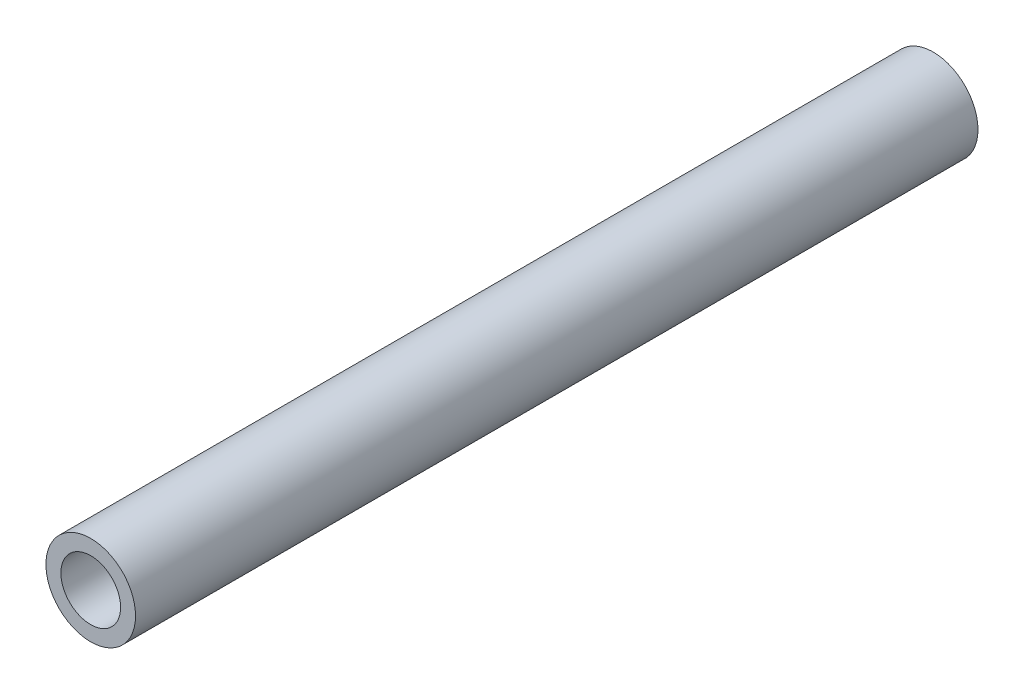
SolidWorks part; units mm, degrees
material "PPE"
ref_plane "Piano frontale" through (0, 0, 0) normal (0, 0, 1) x (1, 0, 0)
ref_plane "Piano superiore" through (0, 0, 0) normal (0, 1, 0) x (1, 0, 0)
ref_plane "Piano destro" through (0, 0, 0) normal (1, 0, 0) x (0, 0, -1)
sketch "Schizzo1" plane through (0, 0, 0) normal (0, 0, 1) x (1, 0, 0)
  circle A0 centre (0, 0) radius 2
  circle A1 centre (0, 0) radius 3
  dimension "D1" = 6
  dimension "D2" = 4
extrude "Estrusione-Estrusione1" add sketch "Schizzo1" along normal blind 56.4
